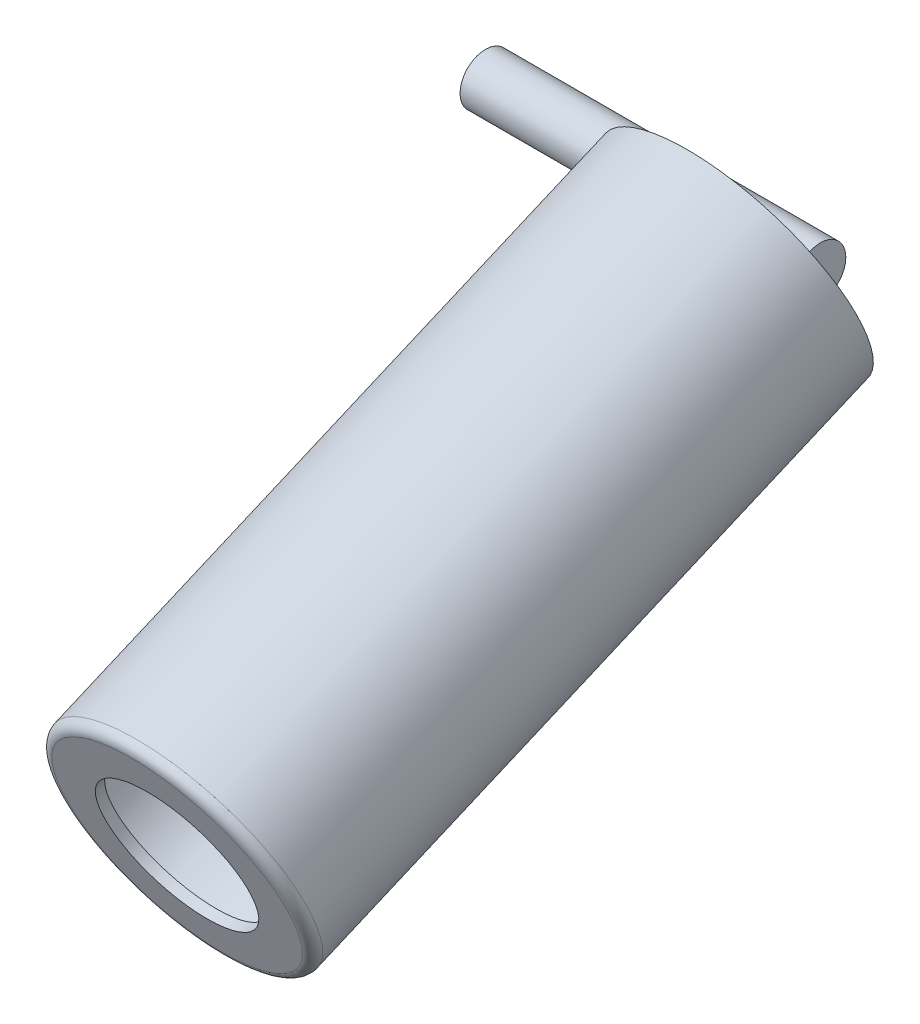
SolidWorks part; units mm, degrees
material "Acero aleado fundido"
ref_plane "Alzado" through (0, 0, 0) normal (0, 0, 1) x (1, 0, 0)
ref_plane "Planta" through (0, 0, 0) normal (0, 1, 0) x (1, 0, 0)
ref_plane "Vista lateral" through (0, 0, 0) normal (1, 0, 0) x (0, 0, -1)
ref_plane "Plano2" through (-995.5144, 0, 0) normal (-1, 0, 0) x (0, 0, 1)
sketch "Croquis2" plane through (-995.5144, 0, 0) normal (-1, 0, 0) x (0, 0, 1)
  circle A0 centre (1824.8242, -360.4928) radius 25
extrude "Saliente-Extruir1" add sketch "Croquis2" against normal blind 200 contours A0
sketch "Croquis3" plane through (-795.5144, 0, 0) normal (1, 0, 0) x (0, 0, -1)
  line L0 (-1824.8242, -360.4928) -> (-2901.0254, -820.7277) construction
  line L1 (-2901.0254, -820.7277) -> (-2960.0056, -682.8098) construction
  dimension "D1" = 150
ref_plane "Plano3" through (0, -1175.6987, 2749.2228) normal (0, -0.3932, 0.9195) x (1, 0, 0)
sketch "Croquis5" plane through (0, -1175.6987, 2749.2228) normal (0, -0.3932, 0.9195) x (1, 0, 0)
  line L0 (-562.2144, -4.1563) -> (-562.2144, 864.9745) construction
  circle A0 centre (-728.8644, 386.068) radius 125
  circle A1 centre (-728.8644, 386.068) radius 110
  dimension "D2" = 250
  dimension "D1" = 166.65
  dimension "D3" = 15
extrude "Saliente-Extruir3" add sketch "Croquis5" against normal blind 600 from offset 550 offset against normal yes
sketch "Croquis6" plane through (0, -959.4379, 2243.5241) normal (0, -0.3932, 0.9195) x (1, 0, 0)
  circle A0 centre (-728.8644, 386.068) radius 125
  circle A1 centre (-728.8644, 386.068) radius 75
  dimension "D1" = 50
extrude "Saliente-Extruir4" add sketch "Croquis6" against normal blind 10
fillet "Redondeo1" radius 10 1 edges at (-728.8644, -719.3983, 2346.1764)
sketch "Croquis7" plane through (0, -723.5169, 1691.8527) normal (0, 0.3932, -0.9195) x (-1, 0, 0)
  circle A0 centre (728.8644, 386.068) radius 125
extrude "Saliente-Extruir5" add sketch "Croquis7" against normal blind 10
sketch "Croquis11" plane through (-795.5144, 0, 0) normal (1, 0, 0) x (0, 0, -1)
  line L0 (-1850.9026, -351.5988) -> (-1842.9008, -343.2231)
  line L1 (-1794.505, -483.4773) -> (-1892.8054, -253.6143) construction
  line L2 (-1824.8242, -385.4928) -> (-1836.4079, -385.4928)
  line L3 (-1836.4079, -385.4928) -> (-1850.9026, -351.5988)
  circle A0 centre (-1824.8242, -360.4928) radius 25 construction
  arc A1 (-1824.8242, -385.4928) -> (-1842.9008, -343.2231) centre (-1824.8242, -360.4928) ccw
extrude "Saliente-Extruir7" add sketch "Croquis11" along normal blind 130
